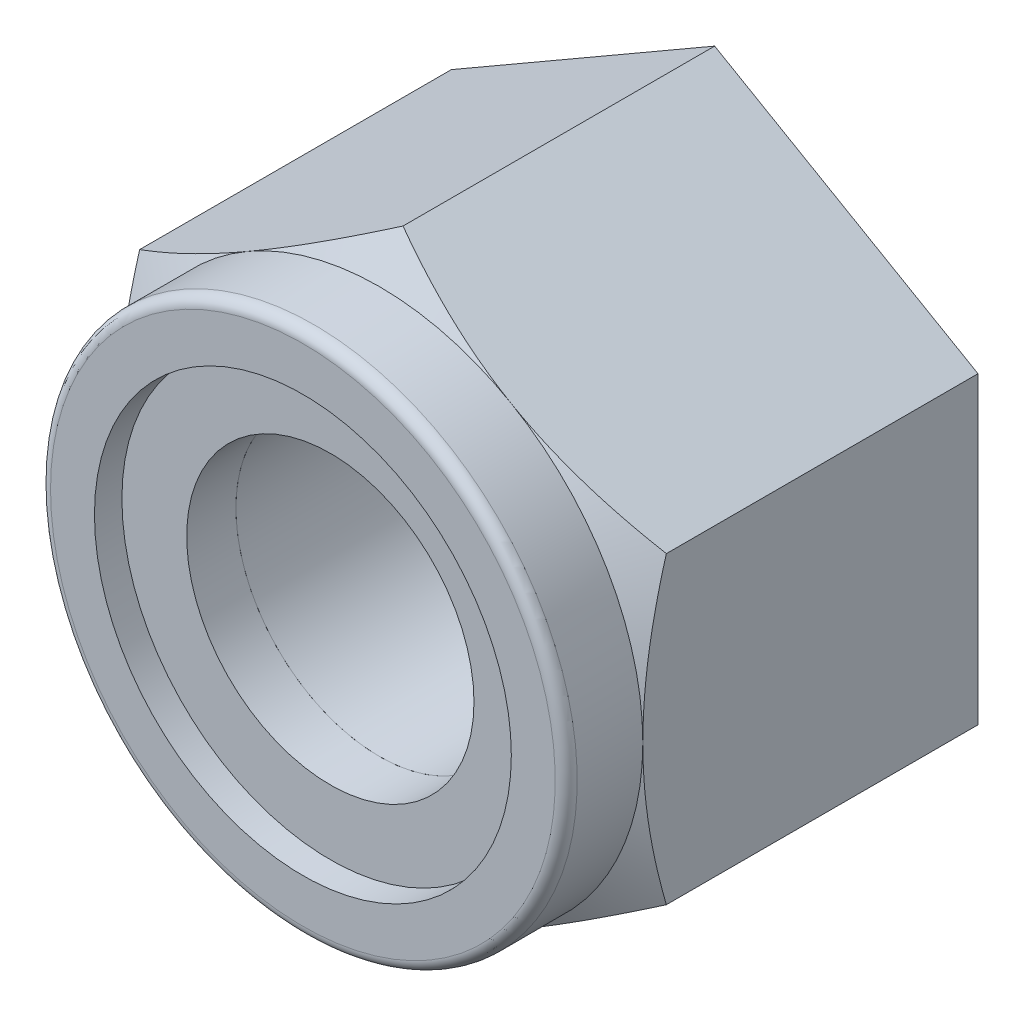
SolidWorks part; units mm, degrees
material "Stainless Steel (ferritic)"
ref_plane "Front" through (0, 0, 0) normal (0, 0, 1) x (1, 0, 0)
ref_plane "Top" through (0, 0, 0) normal (0, 1, 0) x (1, 0, 0)
ref_plane "Right" through (0, 0, 0) normal (1, 0, 0) x (0, 0, -1)
sketch "Sketch1" plane through (0, 0, 0) normal (0, 0, 1) x (1, 0, 0)
  line L1 (0, 3.1754) -> (-2.75, 1.5877)
  line L2 (-2.75, 1.5877) -> (-2.75, -1.5877)
  line L3 (-2.75, -1.5877) -> (0, -3.1754)
  line L4 (0, -3.1754) -> (2.75, -1.5877)
  line L5 (2.75, -1.5877) -> (2.75, 1.5877)
  line L6 (2.75, 1.5877) -> (0, 3.1754)
  circle A0 centre (0, 0) radius 2.75 construction
  dimension "S" = 5.5
extrude "Extrude1" add sketch "Sketch1" along normal blind 3.5
sketch "Sketch2" plane through (0, 0, 0) normal (0, 1, 0) x (1, 0, 0)
  line L0 (2.75, -3.5) -> (3.85, -3.5)
  line L1 (3.85, -3.5) -> (3.85, -2.8649)
  line L2 (3.85, -2.8649) -> (2.75, -3.5)
  line L3 (0, 0) -> (0, -3.5) construction
  dimension "D1" = 30
  dimension "D2" = 1.1
revolve "Cut-Revolve1" cut sketch "Sketch2" angle 360 about L3
sketch "Sketch3" plane through (0, 0, 0) normal (0, 1, 0) x (1, 0, 0)
  line L0 (2.75, -3.5) -> (2.75, -4.3)
  line L1 (2.75, -4.3) -> (2.1767, -4.3)
  line L2 (2.1767, -4.3) -> (2.1767, -4.0133)
  line L3 (2.1767, -4.0133) -> (2.4633, -4.0133)
  line L4 (2.4633, -3.5) -> (2.4633, -4.0133)
  line L5 (1.375, -3.5) -> (2.75, -3.5) construction
  line L6 (2.75, 0) -> (0, 0) construction
  line L7 (2.75, -3.5) -> (2.4633, -3.5)
  line L8 (0, 0) -> (0, -3.5) construction
  line L9 (-1.375, -3.5) -> (1.375, -3.5) construction
  dimension "m" = 4.3
  dimension "D1" = 0.2867
  dimension "D2" = 0.5733
revolve "Revolve1" add sketch "Sketch3" angle 360 about L8
sketch "Sketch4" plane through (0, 0, 0) normal (0, 0, -1) x (-1, 0, 0)
  circle A0 centre (0, 0) radius 1.5
  dimension "d" = 3
sketch "Sketch5" plane through (0, 0, 3.5) normal (0, 0, 1) x (1, 0, 0)
  circle A0 centre (0, 0) radius 2.4633
  circle A1 centre (0, 0) radius 1.5
  circle A2 centre (0, 0) radius 2.4633 construction
  dimension "D1" = 3
extrude "Extrude2" add sketch "Sketch5" along normal up to surface (0.5133 mm away) separate body up to face at (-2.1767, 0, 4.0133)
extrude "Cut-Extrude1" cut sketch "Sketch4" against normal through all
fillet "Fillet2" radius 0.1147 1 edges at (-2.75, 0, 4.3)
equation "\"D2@Sketch2\" = \"S@Sketch1\" / 5"
equation "\"D1@Sketch3\" = \"m@Sketch3\" / 15"
equation "\"D2@Sketch3\" = \"D1@Sketch3\" * 2"
equation "\"D1@Sketch5\" = \"d@Sketch4\""
equation "\"D1@Fillet2\" = \"D2@Sketch3\" / 5"
